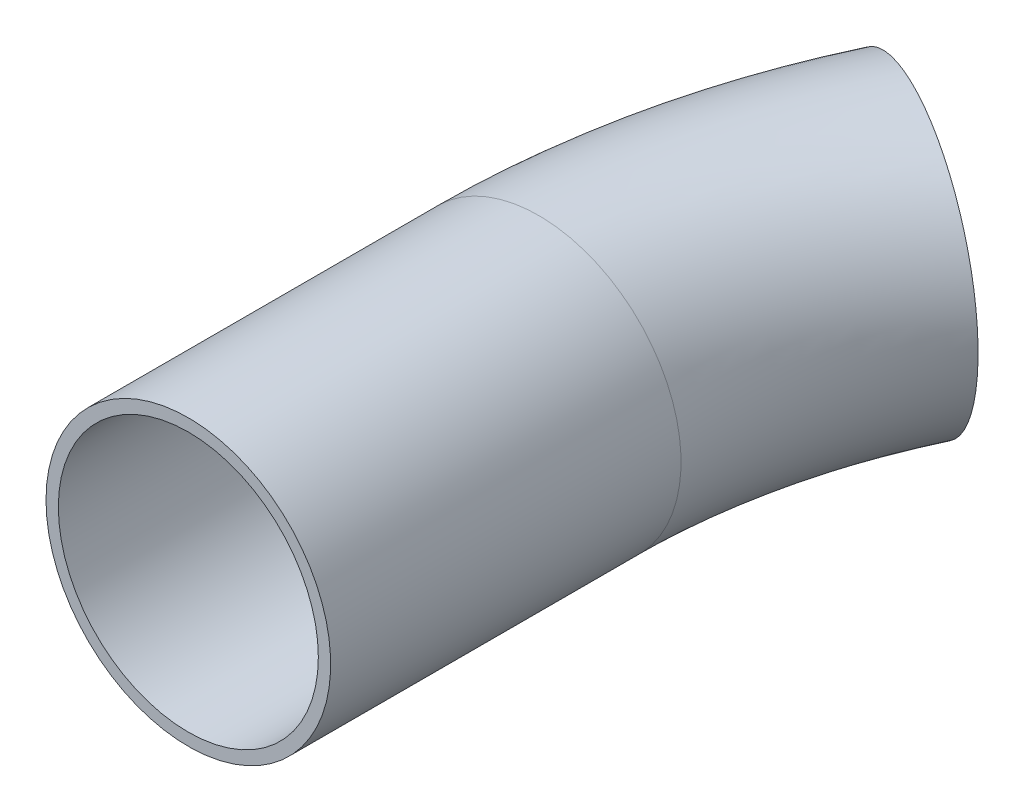
SolidWorks part; units mm, degrees
material "AISI 321 Annealed Stainless Steel (SS)"
ref_plane "Front Plane" through (0, 0, 0) normal (0, 0, 1) x (1, 0, 0)
ref_plane "Top Plane" through (0, 0, 0) normal (0, 1, 0) x (1, 0, 0)
ref_plane "Right Plane" through (0, 0, 0) normal (1, 0, 0) x (0, 0, -1)
sketch "Sketch1" plane through (0, 0, 0) normal (0, 1, 0) x (1, 0, 0)
  line L0 (0, 0) -> (0, 82.6812) construction
  line L1 (-12.6088, 66.679) -> (19.812, 135.89) construction
  line L2 (0, 25.4) -> (0, 72.2915)
  arc A0 (0, 72.2915) -> (9.0373, 112.8886) centre (95.7028, 72.2915) cw
  point P5 (0, 25.4)
  point P6 (9.0373, 112.8886)
  dimension "D1" = 25.1
  dimension "D2" = 19.812
  dimension "D3" = 135.89
  dimension "D4" = 25.4
  dimension "D5" = 25.4
ref_plane "Plane1" through (0, 0, -25.4) normal (0, 0, -1) x (-1, 0, 0)
sketch "Sketch2" plane through (0, 0, -25.4) normal (0, 0, -1) x (-1, 0, 0)
  circle A0 centre (0, 0) radius 19.05
  circle A1 centre (0, 0) radius 17.399
  dimension "D1" = 38.1
  dimension "D2" = 1.651
sweep "Sweep1" add profiles "Sketch2" path "Sketch1"
